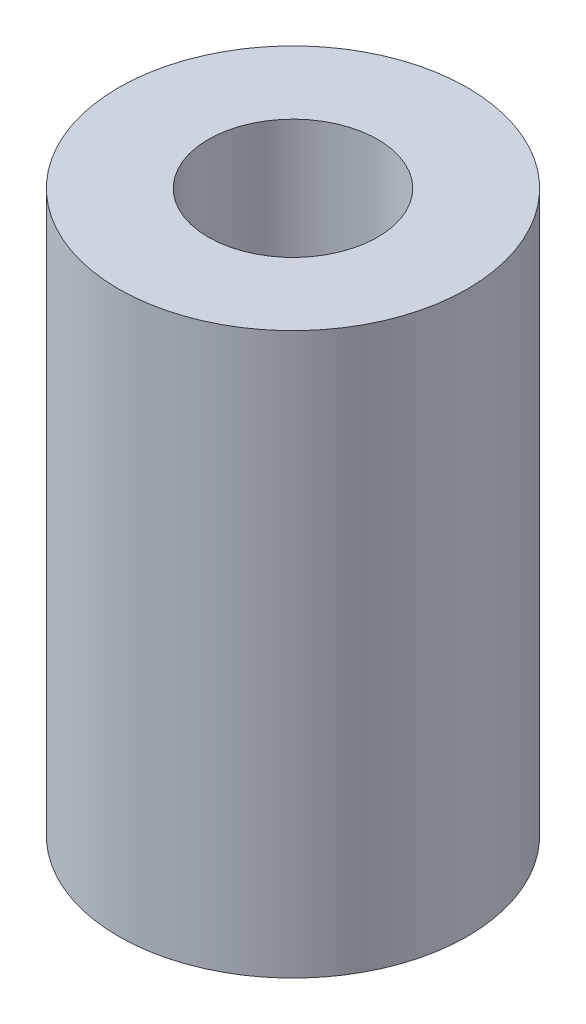
SolidWorks part; units mm, degrees
ref_plane "Front Plane" through (0, 0, 0) normal (0, 0, 1) x (1, 0, 0)
ref_plane "Top Plane" through (0, 0, 0) normal (0, 1, 0) x (1, 0, 0)
ref_plane "Right Plane" through (0, 0, 0) normal (1, 0, 0) x (0, 0, -1)
sketch "Sketch1" plane through (0, 0, 0) normal (0, 1, 0) x (1, 0, 0)
  circle A0 centre (0, 0) radius 3.5
  circle A1 centre (0, 0) radius 1.7
extrude "Boss-Extrude1" add sketch "Sketch1" along normal blind 11.252
